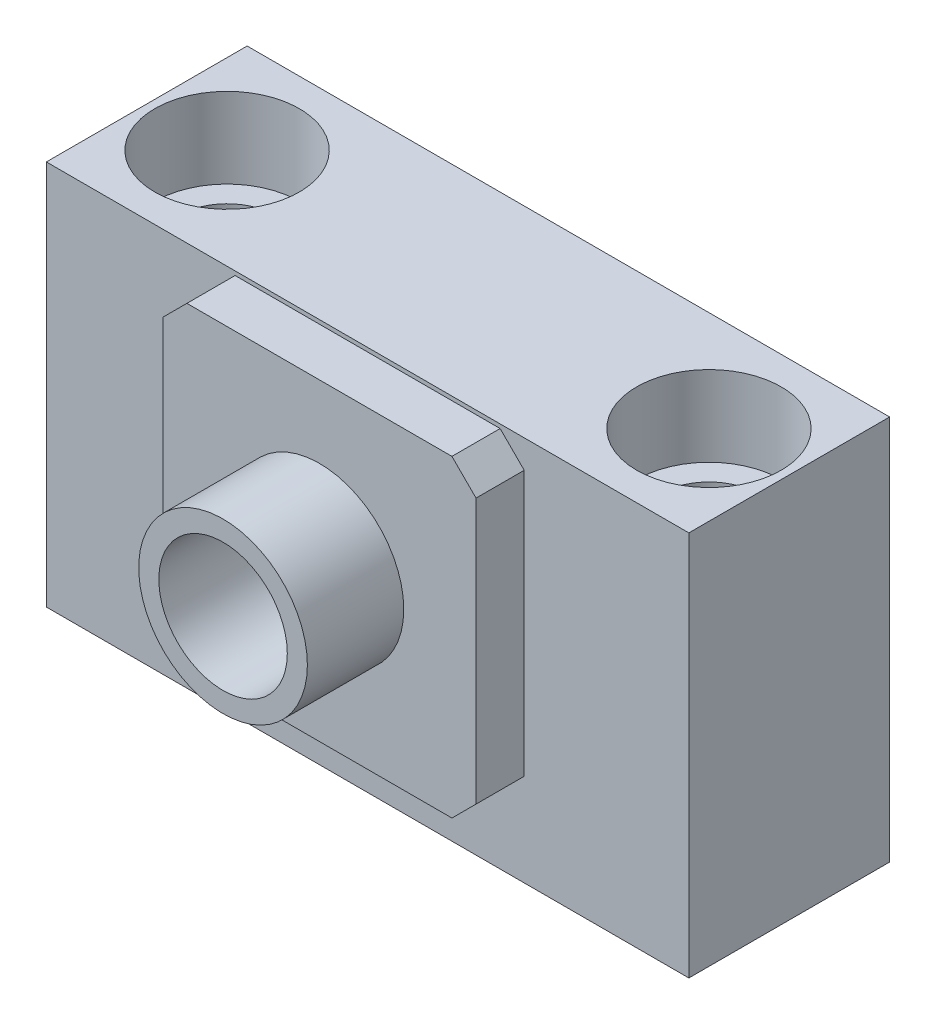
SolidWorks part; units mm, degrees
material "SKD11淬火HRC56-60"
ref_plane "前基準面" through (0, 0, 0) normal (0, 0, 1) x (1, 0, 0)
ref_plane "上基準面" through (0, 0, 0) normal (0, 1, 0) x (1, 0, 0)
ref_plane "右基準面" through (0, 0, 0) normal (1, 0, 0) x (0, 0, -1)
sketch "草图1" plane through (0, 0, 0) normal (0, 0, 1) x (1, 0, 0)
  line L1 (0, 0) -> (80, 0)
  line L2 (0, 0) -> (0, 48)
  line L3 (0, 48) -> (80, 48)
  line L4 (80, 0) -> (80, 48)
  dimension "D1" = 80
  dimension "D2" = 48
extrude "凸台-拉伸1" add sketch "草图1" along normal blind 25
sketch "草图2" plane through (0, 0, 25) normal (0, 0, 1) x (1, 0, 0)
  line L0 (40, 48) -> (40, 0) construction
  line L1 (20.5, 47.5) -> (59.5, 47.5)
  line L2 (20.5, 47.5) -> (20.5, 8.5)
  line L3 (20.5, 8.5) -> (59.5, 8.5)
  line L4 (59.5, 47.5) -> (59.5, 8.5)
  line L5 (80, 48) -> (0, 48) construction
  line L6 (0, 0) -> (80, 0) construction
  line L7 (0, 28) -> (80, 28) construction
  dimension "D1" = 39
  dimension "D2" = 39
  dimension "D3" = 28
extrude "凸台-拉伸2" add sketch "草图2" along normal blind 6
chamfer "倒角1" distance 3 angle 45 4 edges at (20.5, 8.5, 28) (59.5, 8.5, 28) (59.5, 47.5, 28) (20.5, 47.5, 28)
sketch "草图3" plane through (0, 0, 0) normal (0, 0, -1) x (-1, 0, 0)
  line L0 (-40, 0) -> (-40, 48) construction
  line L1 (0, 0) -> (-80, 0) construction
  line L2 (-80, 48) -> (0, 48) construction
  circle A0 centre (-40, 28) radius 7.5
  dimension "D1" = 15
  dimension "D2" = 28
extrude "切除-拉伸1" cut sketch "草图3" against normal through all
sketch "草图4" plane through (0, 0, 0) normal (0, 0, -1) x (-1, 0, 0)
  circle A0 centre (-40, 28) radius 10
  dimension "D1" = 20
extrude "切除-拉伸2" cut sketch "草图4" against normal blind 5
hole_wizard "M10 六角凹头螺钉的柱形沉头孔1" positions "草图6" profile "草图5" counterbore size "M10" standard "ISO" end condition through all
sketch "草图6" plane through (0, 48, 0) normal (0, 1, 0) x (-1, 0, 0)
  line L0 (-40, 25) -> (-40, 0) construction
  line L1 (-80, 25) -> (0, 25) construction
  line L2 (-80, 0) -> (0, 0) construction
  line L3 (0, 12.5) -> (-80, 12.5) construction
  line L4 (0, 25) -> (0, 0) construction
  line L5 (-80, 25) -> (-80, 0) construction
  point P0 (-70, 12.5)
  point P1 (-10, 12.5)
  dimension "D1" = 60
sketch "草图5" plane through (70, 48, 12.5) normal (1, 0, 0) x (0, 0, 1)
  line L0 (0, 0) -> (0, 48)
  line L1 (0, 48) -> (6, 48)
  line L3 (6, 48) -> (6, 10)
  line L4 (6, 10) -> (9, 10)
  line L5 (9, 10) -> (9, 0)
  line L7 (9, 0) -> (0, 0)
  line L11 (0, -6.35) -> (0, 107.95) construction
  dimension "通孔孔直径" = 12
  dimension "通孔孔深度" = 48
  dimension "柱形沉头孔直径" = 18
  dimension "柱形沉头孔深度" = 10
sketch "草图8" plane through (0, 0, 31) normal (0, 0, 1) x (1, 0, 0)
  circle A0 centre (40, 28) radius 10.5
  circle A1 centre (40, 28) radius 8
  dimension "D1" = 16
  dimension "D2" = 21
extrude "凸台-拉伸4" add sketch "草图8" along normal blind 12 separate body
